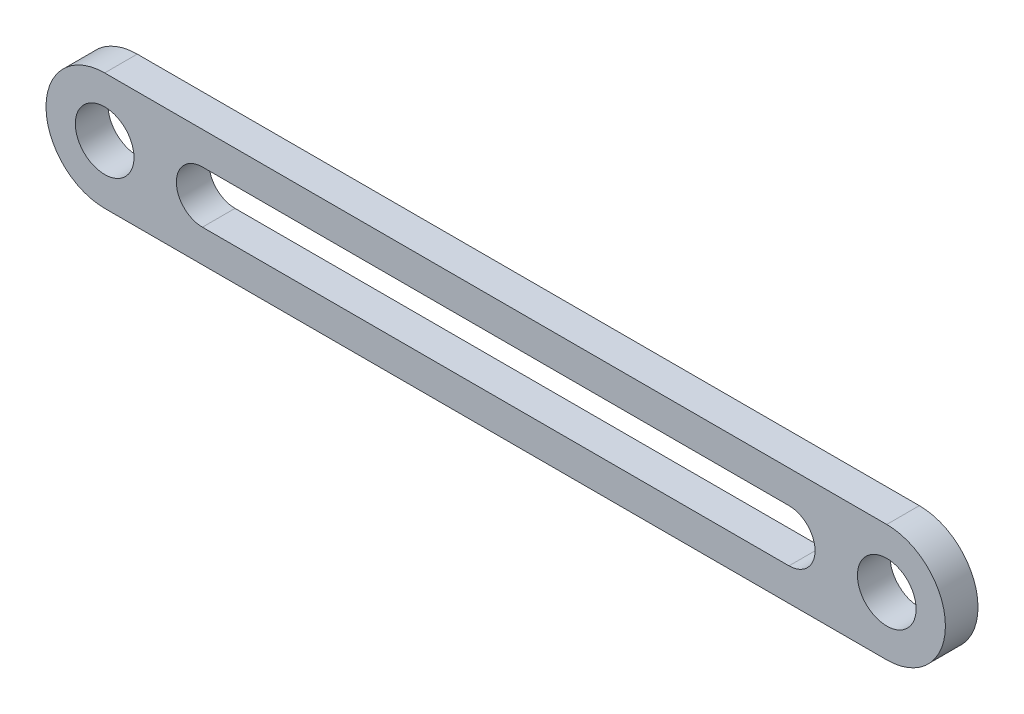
SolidWorks part; units mm, degrees
material "Thornel Mat VMA"
ref_plane "Front Plane" through (0, 0, 0) normal (0, 0, 1) x (1, 0, 0)
ref_plane "Top Plane" through (0, 0, 0) normal (0, 1, 0) x (1, 0, 0)
ref_plane "Right Plane" through (0, 0, 0) normal (1, 0, 0) x (0, 0, -1)
sketch "Sketch1" plane through (0, 0, 0) normal (0, 0, 1) x (1, 0, 0)
  line L0 (-60, 0) -> (60, 0) construction
  line L1 (-60, 9) -> (60, 9)
  line L2 (-60, -9) -> (60, -9)
  arc A0 (-60, 9) -> (-60, -9) centre (-60, 0) ccw
  arc A1 (60, -9) -> (60, 9) centre (60, 0) ccw
  circle A2 centre (-60, 0) radius 4.5
  circle A3 centre (60, 0) radius 4.5
  point P3 (0, 0)
  dimension "D2" = 9
  dimension "D3" = 9
  dimension "D1" = 120
extrude "Boss-Extrude1" add sketch "Sketch1" along normal blind 5
sketch "Sketch2" plane through (0, 0, 5) normal (0, 0, 1) x (1, 0, 0)
  line L0 (-45, 0) -> (45, 0) construction
  line L1 (-45, 4) -> (45, 4)
  line L2 (-45, -4) -> (45, -4)
  arc A0 (-45, 4) -> (-45, -4) centre (-45, 0) ccw
  arc A1 (45, -4) -> (45, 4) centre (45, 0) ccw
  point P3 (0, 0)
  dimension "D1" = 4
  dimension "D2" = 90
extrude "Cut-Extrude1" cut sketch "Sketch2" against normal blind 10
